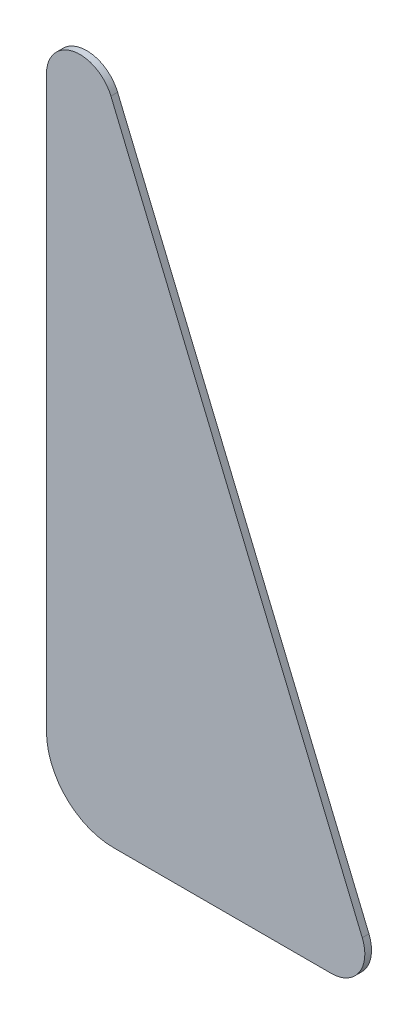
SolidWorks part; units mm, degrees
ref_plane "Front Plane" through (0, 0, 0) normal (0, 0, 1) x (1, 0, 0)
ref_plane "Top Plane" through (0, 0, 0) normal (0, 1, 0) x (1, 0, 0)
ref_plane "Right Plane" through (0, 0, 0) normal (1, 0, 0) x (0, 0, -1)
sketch "Sketch1" plane through (0, 0, 0) normal (0, 0, 1) x (1, 0, 0)
  line L0 (0, 100) -> (0, 950)
  line L1 (96.1538, 969.2308) -> (471.1538, 69.2308)
  line L2 (425, 0) -> (100, 0)
  line L3 (-290.1416, 1000) -> (615.7293, 1000) construction
  arc A0 (0, 100) -> (100, 0) centre (100, 100) ccw
  arc A1 (0, 950) -> (96.1538, 969.2308) centre (50, 950) cw
  arc A2 (471.1538, 69.2308) -> (425, 0) centre (425, 50) cw
  point P8 (0, 0)
  point P11 (0, 1200)
  dimension "D2" = 100
  dimension "D3" = 50
  dimension "D1" = 1000
  dimension "D4" = 1200
extrude "Boss-Extrude1" add sketch "Sketch1" along normal blind 10
